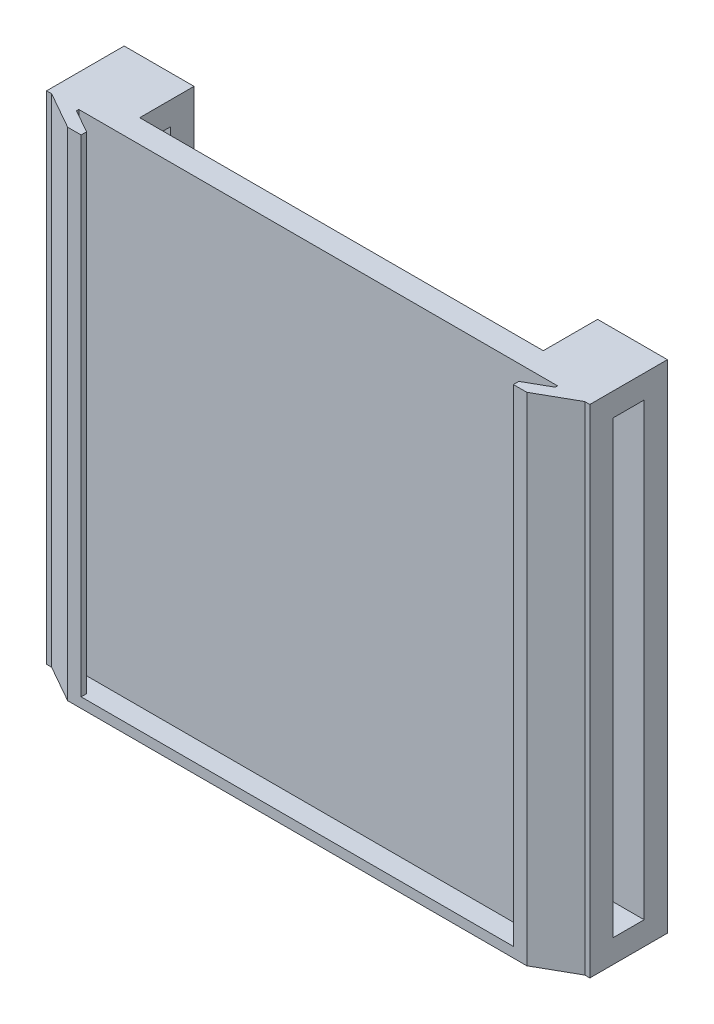
SolidWorks part; units mm, degrees
ref_plane "Front Plane" through (0, 0, 0) normal (0, 0, 1) x (1, 0, 0)
ref_plane "Top Plane" through (0, 0, 0) normal (0, 1, 0) x (1, 0, 0)
ref_plane "Right Plane" through (0, 0, 0) normal (1, 0, 0) x (0, 0, -1)
sketch "Sketch1" plane through (0, 0, 0) normal (0, 0, 1) x (1, 0, 0)
  line L0 (-35, 32) -> (35, -32) construction
  line L1 (-35, 32) -> (35, 32)
  line L2 (-35, 32) -> (-35, -32)
  line L3 (-35, -32) -> (35, -32)
  line L4 (35, 32) -> (35, -32)
  line L5 (-35, -32) -> (35, 32) construction
  point P4 (0, 0)
  dimension "D1" = 70
  dimension "D2" = 64
extrude "Boss-Extrude1" add sketch "Sketch1" along normal blind 10
sketch "Sketch2" plane through (0, 32, 0) normal (0, 1, 0) x (1, 0, 0)
  line L0 (27.8462, -12.7) -> (29.5815, -12.7)
  line L2 (35, -10) -> (-35, -10) construction
  line L3 (27.8462, -12) -> (30.8462, -10.3)
  line L4 (29.5815, -12.7) -> (34.3462, -10)
  line L6 (30.8462, -10.3) -> (30.8462, -10)
  line L8 (30.8462, -10) -> (34.3462, -10)
  line L9 (27.8462, -12) -> (27.8462, -12.7)
  point P0 (30.8462, -10.481)
  point P3 (30.8462, -10.15)
  dimension "D1" = 3.5
  dimension "D2" = 30.8462
  dimension "D3" = 2
  dimension "D4" = 3
  dimension "D5" = 0.3
  dimension "D6" = 0.7
extrude "Boss-Extrude2" add sketch "Sketch2" against normal through all
ref_plane "Plane1" through (0, 0, 0) normal (-1, 0, 0) x (0, 0, 1)
mirror "Mirror1" about plane through (0, 0, 0) normal (-1, 0, 0) of "Boss-Extrude2"
sketch "Sketch3" plane through (0, -32, 0) normal (0, -1, 0) x (1, 0, 0)
  line L0 (-27.8462, 12) -> (-27.8462, 12.7) construction
  line L1 (-30.8462, 10.3) -> (-27.8462, 12) construction
  line L2 (-30.8462, 10) -> (-30.8462, 10.3) construction
  line L3 (-30.8462, 10) -> (30.8462, 10) construction
  line L4 (30.8462, 10) -> (30.8462, 10.3) construction
  line L5 (30.8462, 10.3) -> (27.8462, 12) construction
  line L6 (27.8462, 12) -> (27.8462, 12.7) construction
  line L7 (-27.8462, 12) -> (-27.8462, 12.7)
  line L8 (-30.8462, 10.3) -> (-27.8462, 12)
  line L9 (-30.8462, 10) -> (-30.8462, 10.3)
  line L10 (-30.8462, 10) -> (30.8462, 10)
  line L11 (30.8462, 10) -> (30.8462, 10.3)
  line L12 (30.8462, 10.3) -> (27.8462, 12)
  line L13 (27.8462, 12) -> (27.8462, 12.7)
  line L14 (-27.8462, 12.7) -> (27.8462, 12.7)
extrude "Boss-Extrude3" add sketch "Sketch3" against normal blind 1.3 contours L14 L13 L12 L11 L10 L9 L8 L7
sketch "Sketch5" plane through (0, 32, 0) normal (0, 1, 0) x (1, 0, 0)
  line L0 (35, 0) -> (-35, 0) construction
  line L1 (-26, 0) -> (26, 0)
  line L2 (-26, 0) -> (-26, -7)
  line L3 (-26, -7) -> (26, -7)
  line L4 (26, 0) -> (26, -7)
  line L6 (-26, 0) -> (26, 0) construction
  line L7 (0, -7) -> (0, 0) construction
  dimension "D1" = 7
  dimension "D2" = 52
extrude "Cut-Extrude1" cut sketch "Sketch5" against normal through all
sketch "Sketch6" plane through (35, 0, 0) normal (1, 0, 0) x (0, 0, -1)
  line L4 (0, -32) -> (0, 32) construction
  line L5 (-3, 29) -> (-7, 29)
  line L6 (-3, 29) -> (-3, -29)
  line L7 (-3, -29) -> (-7, -29)
  line L8 (-7, 29) -> (-7, -29)
  line L9 (-10, -32) -> (0, -32) construction
  line L10 (-10, 32) -> (0, 32) construction
  dimension "D1" = 4
  dimension "D2" = 3
  dimension "D3" = 3
  dimension "D4" = 3
extrude "Cut-Extrude2" cut sketch "Sketch6" against normal through all
